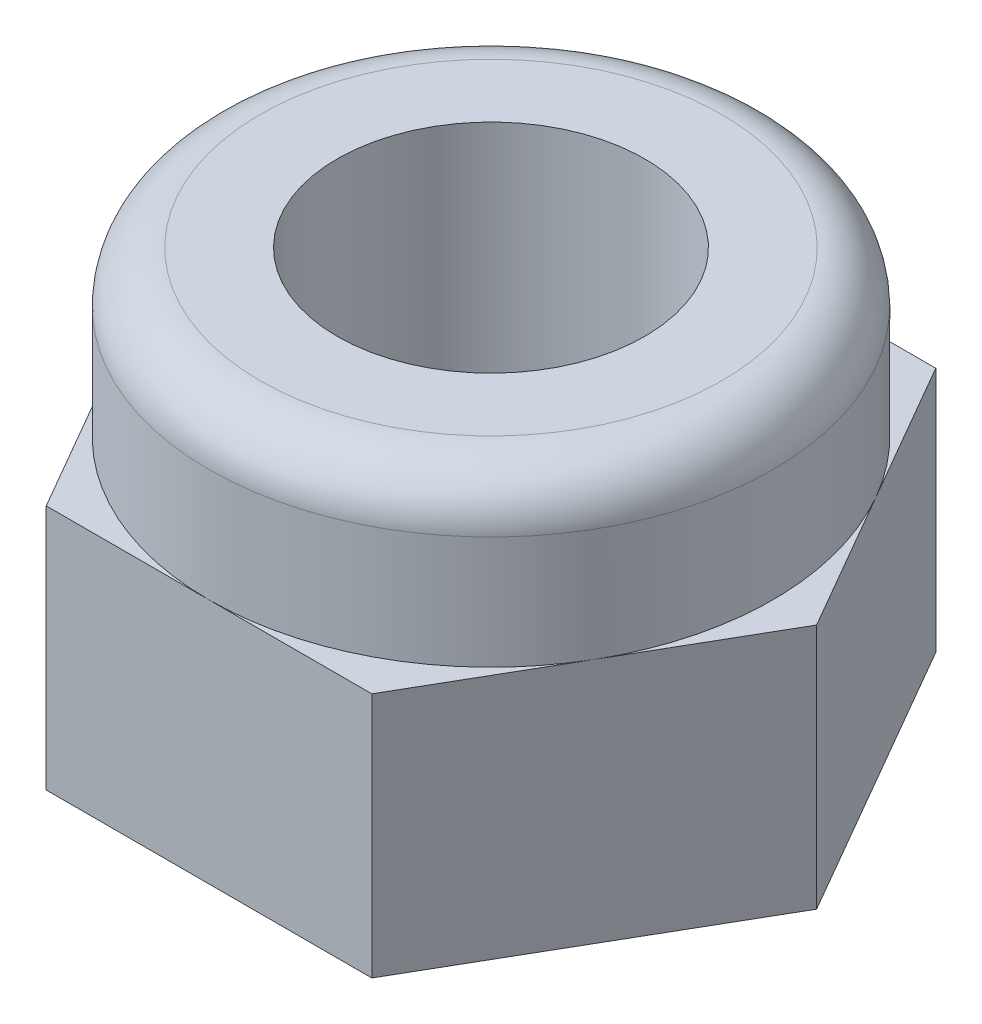
SolidWorks part; units mm, degrees
ref_plane "Plan de face" through (0, 0, 0) normal (0, 0, 1) x (1, 0, 0)
ref_plane "Plan de dessus" through (0, 0, 0) normal (0, 1, 0) x (1, 0, 0)
ref_plane "Plan de droite" through (0, 0, 0) normal (1, 0, 0) x (0, 0, -1)
sketch "Esquisse1" plane through (0, 0, 0) normal (0, 1, 0) x (1, 0, 0)
  line L1 (3.1754, 0) -> (1.5877, 2.75)
  line L2 (1.5877, 2.75) -> (-1.5877, 2.75)
  line L3 (-1.5877, 2.75) -> (-3.1754, 0)
  line L4 (-3.1754, 0) -> (-1.5877, -2.75)
  line L5 (-1.5877, -2.75) -> (1.5877, -2.75)
  line L6 (1.5877, -2.75) -> (3.1754, 0)
  circle A0 centre (0, 0) radius 2.75 construction
  circle A1 centre (0, 0) radius 1.5
  dimension "D1" = 5.5
  dimension "D2" = 3
extrude "Boss.-Extru.1" add sketch "Esquisse1" along normal blind 2.4
sketch "Esquisse2" plane through (0, 2.4, 0) normal (0, 1, 0) x (1, 0, 0)
  line L0 (1.5877, -2.75) -> (3.1754, 0) construction
  circle A0 centre (0, 0) radius 1.5
  circle A1 centre (0, 0) radius 1.5 construction
  circle A2 centre (0, 0) radius 2.75
extrude "Boss.-Extru.2" add sketch "Esquisse2" along normal blind 1.6
fillet "Congé1" radius 0.5 1 edges at (0, 4, 2.75)
